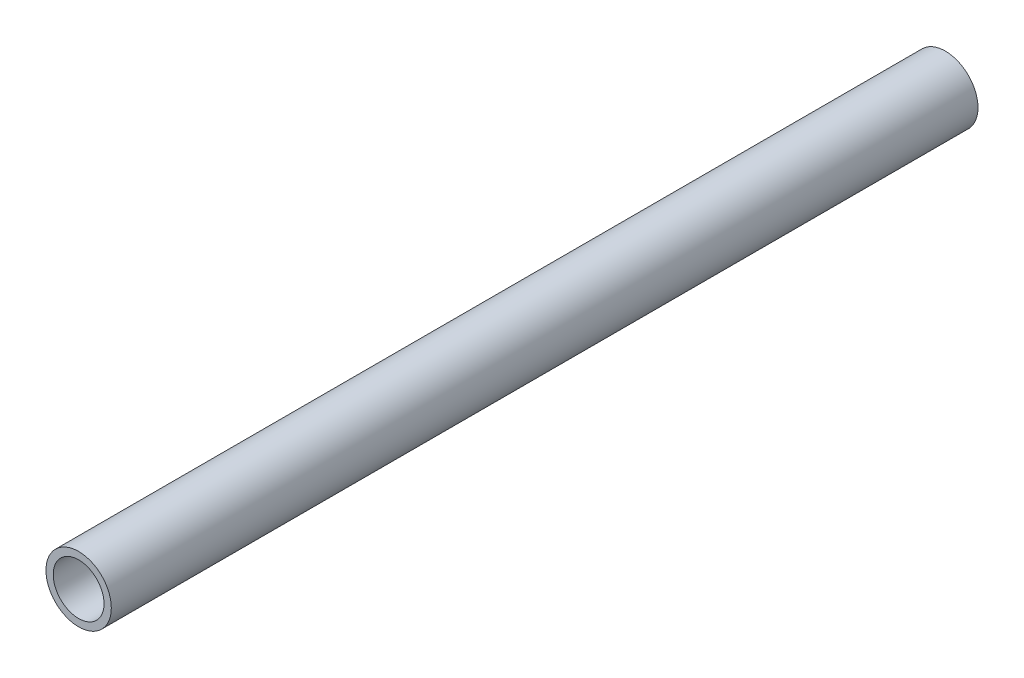
SolidWorks part; units mm, degrees
ref_plane "Front Plane" through (0, 0, 0) normal (0, 0, 1) x (1, 0, 0)
ref_plane "Top Plane" through (0, 0, 0) normal (0, 1, 0) x (1, 0, 0)
ref_plane "Right Plane" through (0, 0, 0) normal (1, 0, 0) x (0, 0, -1)
sketch "Sketch1" plane through (0, 0, 0) normal (0, 0, 1) x (1, 0, 0)
  circle A0 centre (0, 0) radius 7
  circle A1 centre (0, 0) radius 9
  dimension "D1" = 14
  dimension "D2" = 18
extrude "Boss-Extrude1" add sketch "Sketch1" along normal blind 238.63
